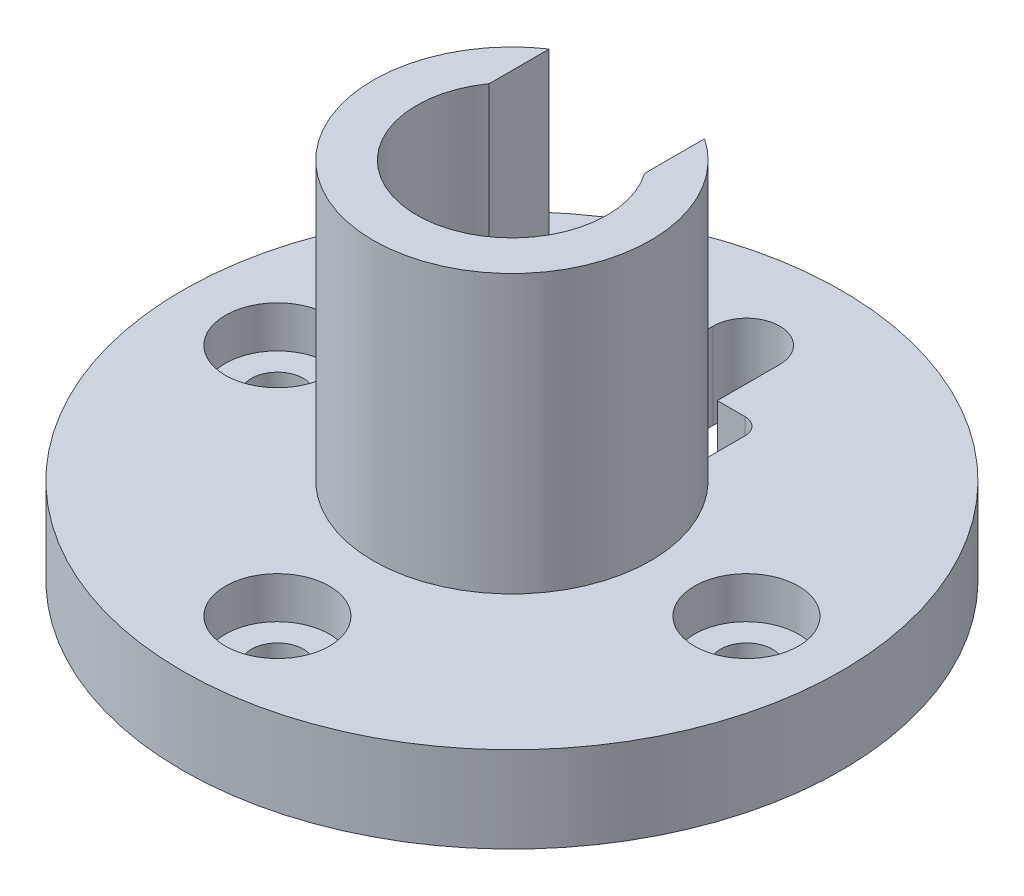
SolidWorks part; units mm, degrees
other "Markup1"
sketch "Sketch6" plane through (-60.325, 66.548, -60.325) normal (0, 1, 0) x (1, 0, 0)
sketch "Sketch8" plane through (-60.325, 66.548, -60.325) normal (0, 1, 0) x (1, 0, 0)
ref_plane "Front Plane" through (0, 0, 0) normal (0, 0, 1) x (1, 0, 0)
ref_plane "Top Plane" through (0, 0, 0) normal (0, 1, 0) x (1, 0, 0)
ref_plane "Right Plane" through (0, 0, 0) normal (1, 0, 0) x (0, 0, -1)
sketch "Sketch1" plane through (0, 0, 0) normal (0, 1, 0) x (1, 0, 0)
  circle A0 centre (0, 0) radius 60.325
  circle A1 centre (0, 0) radius 42.926 construction
  circle A2 centre (0, -42.926) radius 4.7625
  circle A3 centre (42.926, 0) radius 4.7625
  circle A4 centre (-42.926, 0) radius 4.7625
  circle A5 centre (0, 42.926) radius 6.096
  circle A6 centre (0, 0) radius 25.4
  dimension "D1" = 120.65
  dimension "D2" = 85.852
  dimension "D3" = 9.525
  dimension "D4" = 12.192
  dimension "D5" = 50.8
extrude "Boss-Extrude1" add sketch "Sketch1" along normal blind 15.748 contours A0
sketch "Sketch2" plane through (0, 15.748, 0) normal (0, 1, 0) x (1, 0, 0)
  circle A0 centre (0, 0) radius 42.926 construction
  circle A1 centre (0, -42.926) radius 9.525
  circle A2 centre (42.926, 0) radius 9.525
  circle A3 centre (-42.926, 0) radius 9.525
  dimension "D1" = 85.852
  dimension "D2" = 19.05
extrude "Cut-Extrude1" cut sketch "Sketch2" against normal blind 7.62
sketch "Sketch3" plane through (0, 8.128, 0) normal (0, 1, 0) x (1, 0, 0)
  circle A0 centre (-42.926, 0) radius 4.7625
  circle A1 centre (42.926, 0) radius 4.7625
  circle A2 centre (0, -42.926) radius 4.7625
  dimension "D1" = 9.525
extrude "Cut-Extrude2" cut sketch "Sketch3" against normal through all
sketch "Sketch4" plane through (0, 15.748, 0) normal (0, 1, 0) x (1, 0, 0)
  circle A0 centre (0, 0) radius 25.4
  dimension "D1" = 50.8
extrude "Boss-Extrude2" add sketch "Sketch4" along normal blind 50.8 contours A0
sketch "Sketch5" plane through (0, 66.548, 0) normal (0, 1, 0) x (1, 0, 0)
  circle A0 centre (0, 0) radius 17.4244
  dimension "D1" = 34.8488
extrude "Cut-Extrude3" cut sketch "Sketch5" against normal through all
ref_plane "Plane1" through (0, 66.548, 0) normal (0, 1, 0) x (1, 0, 0)
sketch "Sketch7" plane through (0, 66.548, 0) normal (0, 1, 0) x (1, 0, 0)
  line L0 (0, -27.7782) -> (0, 26.9878) construction
  line L1 (-27.2136, 0) -> (27.2136, 0) construction
  line L2 (-6.096, 42.926) -> (-6.096, 31.496)
  line L3 (-14.224, 31.496) -> (-6.096, 31.496)
  line L4 (-14.224, 31.496) -> (-14.224, 0)
  line L5 (-14.224, 0) -> (14.224, 0)
  line L6 (14.224, 31.496) -> (14.224, 0)
  line L7 (6.096, 42.926) -> (6.096, 31.496)
  line L8 (6.096, 31.496) -> (14.224, 31.496)
  circle A2 centre (0, 0) radius 42.926 construction
  arc A3 (6.096, 42.926) -> (-6.096, 42.926) centre (0, 42.926) ccw
  dimension "D4" = 85.852
  dimension "D5" = 12.192
  dimension "D1" = 14.224
  dimension "D2" = 28.448
  dimension "D3" = 31.496
extrude "Cut-Extrude4" cut sketch "Sketch7" against normal through all
fillet "Fillet1" radius 3.048 2 edges at (14.224, 7.874, -31.496) (-14.224, 7.874, -31.496)
